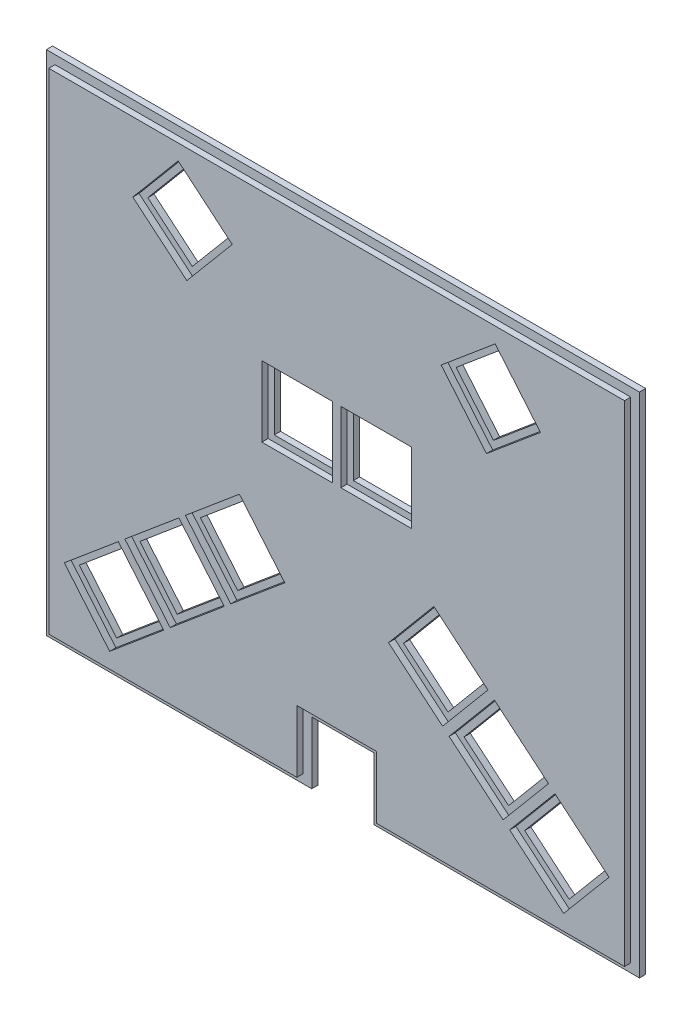
SolidWorks part; units mm, degrees
ref_plane "Alzado" through (0, 0, 0) normal (0, 0, 1) x (1, 0, 0)
ref_plane "Planta" through (0, 0, 0) normal (0, 1, 0) x (1, 0, 0)
ref_plane "Vista lateral" through (0, 0, 0) normal (1, 0, 0) x (0, 0, -1)
sketch "Model" plane through (0, 0, 0) normal (0, 0, 1) x (1, 0, 0)
  line L0 (0, 114.3975) -> (135.05, 114.3975)
  line L1 (135.05, 114.3975) -> (135.05, 0)
  line L2 (135.05, 0) -> (0, 0)
  line L3 (0, 0) -> (0, 114.3975)
  line L4 (51, 35) -> (65, 35)
  line L5 (65, 35) -> (65, 49)
  line L6 (65, 49) -> (51, 49)
  line L7 (51, 49) -> (51, 35)
  line L8 (67.525, 0) -> (67.525, 114.3975) construction
  line L9 (18.5931, 87.4278) -> (29.3178, 78.4288)
  line L10 (29.3178, 78.4288) -> (38.3168, 89.1534)
  line L11 (38.3168, 89.1534) -> (27.5922, 98.1524)
  line L12 (103.8144, 23.7236) -> (114.539, 14.7246)
  line L13 (94.8154, 12.999) -> (103.8144, 23.7236)
  line L14 (105.54, 4) -> (94.8154, 12.999)
  line L15 (114.539, 14.7246) -> (105.54, 4)
  line L16 (27.5922, 98.1524) -> (18.5931, 87.4278)
  line L17 (33.1863, 75.1827) -> (43.9109, 66.1836)
  line L18 (43.9109, 66.1836) -> (52.9099, 76.9083)
  line L19 (52.9099, 76.9083) -> (42.1853, 85.9073)
  line L20 (42.1853, 85.9073) -> (33.1863, 75.1827)
  line L21 (20.511, 14.7246) -> (29.51, 4)
  line L22 (29.51, 4) -> (40.2346, 12.999)
  line L23 (40.2346, 12.999) -> (31.2356, 23.7236)
  line L24 (31.2356, 23.7236) -> (20.511, 14.7246)
  line L25 (84.05, 49) -> (84.05, 35)
  line L26 (70.05, 49) -> (84.05, 49)
  line L27 (70.05, 35) -> (70.05, 49)
  line L28 (84.05, 35) -> (70.05, 35)
  line L29 (92.8647, 85.9073) -> (101.8637, 75.1827)
  line L30 (82.1401, 76.9083) -> (92.8647, 85.9073)
  line L31 (91.1391, 66.1836) -> (82.1401, 76.9083)
  line L32 (101.8637, 75.1827) -> (91.1391, 66.1836)
  line L33 (107.4578, 98.1524) -> (116.4569, 87.4278)
  line L34 (96.7332, 89.1534) -> (107.4578, 98.1524)
  line L35 (105.7322, 78.4288) -> (96.7332, 89.1534)
  line L36 (4, 99.6729) -> (14.7246, 90.6739)
  line L37 (14.7246, 90.6739) -> (23.7236, 101.3985)
  line L38 (23.7236, 101.3985) -> (12.999, 110.3975)
  line L39 (12.999, 110.3975) -> (4, 99.6729)
  line L40 (116.4569, 87.4278) -> (105.7322, 78.4288)
  line L41 (120.3254, 90.6739) -> (111.3264, 101.3985)
  line L42 (131.05, 99.6729) -> (120.3254, 90.6739)
  line L43 (122.051, 110.3975) -> (131.05, 99.6729)
  line L44 (4, 99.6729) -> (0, 99.6729) construction
  line L45 (111.3264, 101.3985) -> (122.051, 110.3975)
  line L46 (27.5922, 98.1524) -> (29.3178, 78.4288) construction
  line L47 (107.4578, 98.1524) -> (105.7322, 78.4288) construction
  line L48 (51, 35) -> (65, 49) construction
  line L49 (70.05, 49) -> (84.05, 35) construction
  line L50 (20.511, 14.7246) -> (40.2346, 12.999) construction
  line L51 (4, 99.6729) -> (0, 103.0293) construction
  line L52 (103.8144, 23.7236) -> (105.54, 4) construction
  line L54 (-3.95, 118.3475) -> (139, 118.3475)
  line L55 (-3.95, 118.3475) -> (-3.95, -3.95)
  line L56 (-3.95, -3.95) -> (139, -3.95)
  line L57 (139, 118.3475) -> (139, -3.95)
  line L58 (-3.95, 118.3475) -> (139, -3.95) construction
  line L59 (-3.95, -3.95) -> (139, 118.3475) construction
  point P8 (28.455, 88.2906)
  point P23 (106.595, 88.2906)
  point P50 (58, 42)
  point P51 (77.05, 42)
  point P52 (30.3728, 13.8618)
  point P54 (104.6772, 13.8618)
  point P55 (67.525, 57.1988)
  dimension "D1" = 14
  dimension "D8" = 4
  dimension "D2" = 4
  dimension "D3" = 40
  dimension "D4" = 114.3975
  dimension "D5" = 5.05
  dimension "D9" = 5.05
  dimension "D10" = 50
  dimension "D6" = 4
  dimension "D11" = 29.51
  dimension "D7" = 35
  dimension "D12" = 51
  dimension "D13" = 5.05
  dimension "D14" = 135.05
  dimension "D15" = 28.455
  dimension "D16" = 26.1069
  dimension "D17" = 106.595
  dimension "D18" = 26.1069
  dimension "D19" = 19.05
  dimension "D20" = 72.3975
  dimension "D21" = 67.525
  dimension "D22" = 100.5357
  dimension "D23" = 30.3728
  dimension "D24" = 104.6772
  dimension "D25" = 3.95
  dimension "D26" = 3.95
extrude "Saliente-Extruir1" add sketch "Model" along normal mid plane 1.5 contours L3 L2 L1 L0 L39 L38 L37 L36 L24 L23 L22 L21 L20 L19 L18 L17 L16 L11 L10 L9 L7 L6 L5 L4 L12 L15 L14 L13 L25 L28 L27 L26 L29 L32 L31 L30 L33 L40 L35 L34 L41 | L57 L54 L55 L56 L2 L3 L0 L1
sketch "Croquis1" plane through (0, 0, 0.75) normal (0, 0, 1) x (1, 0, 0)
  line L0 (-3.95, 118.3475) -> (-3.95, -3.95) construction
  line L2 (-3.95, 118.3475) -> (139, 118.3475) construction
  point P0 (12.55, 80.9213)
  dimension "D1" = 16.5
  dimension "D3" = 37.4262
sketch "Croquis2" plane through (0, 0, 0.75) normal (0, 0, 1) x (1, 0, 0)
  line L0 (-3.95, 118.3475) -> (139, 118.3475) construction
  line L1 (60.025, 133.3475) -> (75.025, 133.3475)
  line L2 (60.025, 133.3475) -> (60.025, 103.3475)
  line L3 (60.025, 103.3475) -> (75.025, 103.3475)
  line L4 (75.025, 133.3475) -> (75.025, 103.3475)
  line L5 (60.025, 133.3475) -> (75.025, 103.3475) construction
  line L6 (60.025, 103.3475) -> (75.025, 133.3475) construction
  point P0 (67.525, 118.3475)
  dimension "D1" = 15
  dimension "D2" = 15
extrude "Cortar-Extruir1" cut sketch "Croquis2" against normal through all
sketch "Croquis3" plane through (0, 0, -0.75) normal (0, 0, -1) x (-1, 0, 0)
  line L4 (-4, 99.6729) -> (-12.999, 110.3975)
  line L5 (-14.7246, 90.6739) -> (-4, 99.6729)
  line L6 (-23.7236, 101.3985) -> (-14.7246, 90.6739)
  line L7 (-12.999, 110.3975) -> (-23.7236, 101.3985)
  line L8 (-4, 99.6729) -> (-12.999, 110.3975)
  line L9 (-14.7246, 90.6739) -> (-4, 99.6729)
  line L10 (-23.7236, 101.3985) -> (-14.7246, 90.6739)
  line L11 (-12.999, 110.3975) -> (-23.7236, 101.3985)
  line L12 (-120.3254, 90.6739) -> (-111.3264, 101.3985)
  line L13 (-131.05, 99.6729) -> (-120.3254, 90.6739)
  line L14 (-122.051, 110.3975) -> (-131.05, 99.6729)
  line L15 (-111.3264, 101.3985) -> (-122.051, 110.3975)
  line L16 (-120.3254, 90.6739) -> (-111.3264, 101.3985)
  line L17 (-131.05, 99.6729) -> (-120.3254, 90.6739)
  line L18 (-122.051, 110.3975) -> (-131.05, 99.6729)
  line L19 (-111.3264, 101.3985) -> (-122.051, 110.3975)
  line L20 (-20.511, 14.7246) -> (-31.2356, 23.7236)
  line L21 (-29.51, 4) -> (-20.511, 14.7246)
  line L22 (-40.2346, 12.999) -> (-29.51, 4)
  line L23 (-31.2356, 23.7236) -> (-40.2346, 12.999)
  line L24 (-20.511, 14.7246) -> (-31.2356, 23.7236)
  line L25 (-29.51, 4) -> (-20.511, 14.7246)
  line L26 (-40.2346, 12.999) -> (-29.51, 4)
  line L27 (-31.2356, 23.7236) -> (-40.2346, 12.999)
  line L28 (-107.4578, 98.1524) -> (-116.4569, 87.4278)
  line L29 (-96.7332, 89.1534) -> (-107.4578, 98.1524)
  line L30 (-105.7322, 78.4288) -> (-96.7332, 89.1534)
  line L31 (-116.4569, 87.4278) -> (-105.7322, 78.4288)
  line L32 (-107.4578, 98.1524) -> (-116.4569, 87.4278)
  line L33 (-96.7332, 89.1534) -> (-107.4578, 98.1524)
  line L34 (-105.7322, 78.4288) -> (-96.7332, 89.1534)
  line L35 (-116.4569, 87.4278) -> (-105.7322, 78.4288)
  line L36 (-92.8647, 85.9073) -> (-101.8637, 75.1827)
  line L37 (-82.1401, 76.9083) -> (-92.8647, 85.9073)
  line L38 (-91.1391, 66.1836) -> (-82.1401, 76.9083)
  line L39 (-101.8637, 75.1827) -> (-91.1391, 66.1836)
  line L40 (-92.8647, 85.9073) -> (-101.8637, 75.1827)
  line L41 (-82.1401, 76.9083) -> (-92.8647, 85.9073)
  line L42 (-91.1391, 66.1836) -> (-82.1401, 76.9083)
  line L43 (-101.8637, 75.1827) -> (-91.1391, 66.1836)
  line L44 (-84.05, 49) -> (-84.05, 35)
  line L45 (-70.05, 49) -> (-84.05, 49)
  line L46 (-70.05, 35) -> (-70.05, 49)
  line L47 (-84.05, 35) -> (-70.05, 35)
  line L48 (-84.05, 49) -> (-84.05, 35)
  line L49 (-70.05, 49) -> (-84.05, 49)
  line L50 (-70.05, 35) -> (-70.05, 49)
  line L51 (-84.05, 35) -> (-70.05, 35)
  line L52 (-103.8144, 23.7236) -> (-114.539, 14.7246)
  line L53 (-94.8154, 12.999) -> (-103.8144, 23.7236)
  line L54 (-105.54, 4) -> (-94.8154, 12.999)
  line L55 (-114.539, 14.7246) -> (-105.54, 4)
  line L56 (-103.8144, 23.7236) -> (-114.539, 14.7246)
  line L57 (-94.8154, 12.999) -> (-103.8144, 23.7236)
  line L58 (-105.54, 4) -> (-94.8154, 12.999)
  line L59 (-114.539, 14.7246) -> (-105.54, 4)
  line L60 (-51, 35) -> (-51, 49)
  line L61 (-65, 35) -> (-51, 35)
  line L62 (-65, 49) -> (-65, 35)
  line L63 (-51, 49) -> (-65, 49)
  line L64 (-51, 35) -> (-51, 49)
  line L65 (-65, 35) -> (-51, 35)
  line L66 (-65, 49) -> (-65, 35)
  line L67 (-51, 49) -> (-65, 49)
  line L68 (-18.5931, 87.4278) -> (-27.5922, 98.1524)
  line L69 (-29.3178, 78.4288) -> (-18.5931, 87.4278)
  line L70 (-38.3168, 89.1534) -> (-29.3178, 78.4288)
  line L71 (-27.5922, 98.1524) -> (-38.3168, 89.1534)
  line L72 (-18.5931, 87.4278) -> (-27.5922, 98.1524)
  line L73 (-29.3178, 78.4288) -> (-18.5931, 87.4278)
  line L74 (-38.3168, 89.1534) -> (-29.3178, 78.4288)
  line L75 (-27.5922, 98.1524) -> (-38.3168, 89.1534)
  line L76 (-33.1863, 75.1827) -> (-42.1853, 85.9073)
  line L77 (-43.9109, 66.1836) -> (-33.1863, 75.1827)
  line L78 (-52.9099, 76.9083) -> (-43.9109, 66.1836)
  line L79 (-42.1853, 85.9073) -> (-52.9099, 76.9083)
  line L80 (-33.1863, 75.1827) -> (-42.1853, 85.9073)
  line L81 (-43.9109, 66.1836) -> (-33.1863, 75.1827)
  line L82 (-52.9099, 76.9083) -> (-43.9109, 66.1836)
  line L83 (-42.1853, 85.9073) -> (-52.9099, 76.9083)
  line L88 (-57.925, 101.2475) -> (-77.125, 101.2475)
  line L89 (-77.125, 101.2475) -> (-77.125, 116.2475)
  line L90 (-77.125, 116.2475) -> (-136.9, 116.2475)
  line L91 (-136.9, 116.2475) -> (-136.9, -1.85)
  line L92 (-136.9, -1.85) -> (1.85, -1.85)
  line L93 (1.85, -1.85) -> (1.85, 116.2475)
  line L94 (1.85, 116.2475) -> (-57.925, 116.2475)
  line L95 (-57.925, 116.2475) -> (-57.925, 101.2475)
  line L96 (-60.025, 103.3475) -> (-75.025, 103.3475)
  line L97 (-75.025, 103.3475) -> (-75.025, 118.3475)
  line L98 (-75.025, 118.3475) -> (-139, 118.3475)
  line L99 (-139, 118.3475) -> (-139, -3.95)
  line L100 (-139, -3.95) -> (3.95, -3.95)
  line L101 (3.95, -3.95) -> (3.95, 118.3475)
  line L102 (3.95, 118.3475) -> (-60.025, 118.3475)
  line L103 (-60.025, 118.3475) -> (-60.025, 103.3475)
  line L104 (-60.025, 103.3475) -> (-75.025, 103.3475)
  line L105 (-75.025, 103.3475) -> (-75.025, 118.3475)
  line L106 (-75.025, 118.3475) -> (-139, 118.3475)
  line L107 (-139, 118.3475) -> (-139, -3.95)
  line L108 (-139, -3.95) -> (3.95, -3.95)
  line L109 (3.95, -3.95) -> (3.95, 118.3475)
  line L110 (3.95, 118.3475) -> (-60.025, 118.3475)
  line L111 (-60.025, 118.3475) -> (-60.025, 103.3475)
  line L112 (-29.3251, 1.8868) -> (-18.3977, 14.9095)
  line L113 (-18.3977, 14.9095) -> (-31.4205, 25.8369)
  line L114 (-31.4205, 25.8369) -> (-42.3479, 12.8141)
  line L115 (-42.3479, 12.8141) -> (-29.3251, 1.8868)
  line L116 (-49.5, 33.5) -> (-49.5, 50.5)
  line L117 (-49.5, 50.5) -> (-66.5, 50.5)
  line L118 (-66.5, 50.5) -> (-66.5, 33.5)
  line L119 (-66.5, 33.5) -> (-49.5, 33.5)
  line L120 (-68.55, 33.5) -> (-68.55, 50.5)
  line L121 (-68.55, 50.5) -> (-85.55, 50.5)
  line L122 (-85.55, 50.5) -> (-85.55, 33.5)
  line L123 (-85.55, 33.5) -> (-68.55, 33.5)
  line L124 (-105.7249, 1.8868) -> (-92.7021, 12.8141)
  line L125 (-92.7021, 12.8141) -> (-103.6295, 25.8369)
  line L126 (-103.6295, 25.8369) -> (-116.6523, 14.9095)
  line L127 (-116.6523, 14.9095) -> (-105.7249, 1.8868)
  line L128 (-1.8868, 99.488) -> (-12.8141, 112.5108)
  line L129 (-12.8141, 112.5108) -> (-25.8369, 101.5834)
  line L130 (-25.8369, 101.5834) -> (-14.9095, 88.5606)
  line L131 (-14.9095, 88.5606) -> (-1.8868, 99.488)
  line L132 (-16.4799, 87.2429) -> (-27.4073, 100.2656)
  line L133 (-27.4073, 100.2656) -> (-40.43, 89.3383)
  line L134 (-40.43, 89.3383) -> (-29.5027, 76.3155)
  line L135 (-29.5027, 76.3155) -> (-16.4799, 87.2429)
  line L136 (-31.073, 74.9978) -> (-42.0004, 88.0205)
  line L137 (-42.0004, 88.0205) -> (-55.0232, 77.0932)
  line L138 (-55.0232, 77.0932) -> (-44.0958, 64.0704)
  line L139 (-44.0958, 64.0704) -> (-31.073, 74.9978)
  line L140 (-90.9542, 64.0704) -> (-80.0268, 77.0932)
  line L141 (-80.0268, 77.0932) -> (-93.0496, 88.0205)
  line L142 (-93.0496, 88.0205) -> (-103.977, 74.9978)
  line L143 (-103.977, 74.9978) -> (-90.9542, 64.0704)
  line L144 (-105.5473, 76.3155) -> (-94.62, 89.3383)
  line L145 (-94.62, 89.3383) -> (-107.6427, 100.2656)
  line L146 (-107.6427, 100.2656) -> (-118.5701, 87.2429)
  line L147 (-118.5701, 87.2429) -> (-105.5473, 76.3155)
  line L148 (-120.1405, 88.5606) -> (-109.2131, 101.5834)
  line L149 (-109.2131, 101.5834) -> (-122.2359, 112.5108)
  line L150 (-122.2359, 112.5108) -> (-133.1632, 99.488)
  line L151 (-133.1632, 99.488) -> (-120.1405, 88.5606)
  dimension "D1" = 0
  dimension "D2" = 0
  dimension "D3" = 0
  dimension "D4" = 0
  dimension "D5" = 0
  dimension "D6" = 0
  dimension "D7" = 0
  dimension "D8" = 0
  dimension "D9" = 0
  dimension "D10" = 0
  dimension "D11" = 0
  dimension "D12" = 2.1
  dimension "D13" = 1.5
extrude "Saliente-Extruir2" add sketch "Croquis3" along normal blind 1.5 contours L94 L95 L88 L89 L90 L91 L92 L93 L151 L150 L149 L148 L147 L146 L145 L144 L143 L142 L141 L140 L139 L138 L137 L136 L135 L134 L133 L132 L131 L130 L129 L128 L127 L126 L125 L124 L123 L122 L121 L120 L119 L118
move or copy body "Sólido-Mover/Copiar1" bodies to move or copy 105 copy no rotation origin (0, 57.1988, -0.75) rotation axis (1, 0, 0) rotation angle 180
equation "\"G\"= 3.95"
equation "\"D26@Model\"=\"G\""
equation "\"D25@Model\"=\"G\""
